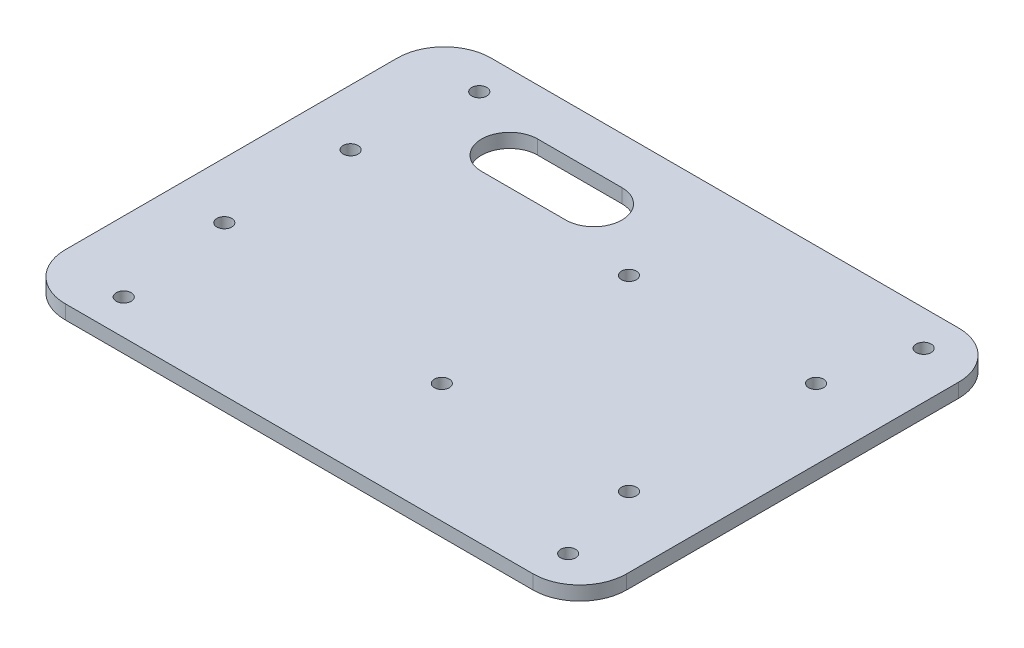
SolidWorks part; units mm, degrees
ref_plane "Front Plane" through (0, 0, 0) normal (0, 0, 1) x (1, 0, 0)
ref_plane "Top Plane" through (0, 0, 0) normal (0, 1, 0) x (1, 0, 0)
ref_plane "Right Plane" through (0, 0, 0) normal (1, 0, 0) x (0, 0, -1)
sketch "Çizim1" plane through (0, 0, 0) normal (0, 1, 0) x (1, 0, 0)
  line L1 (-50, -45.5) -> (50, -45.5)
  line L2 (-60, -35.5) -> (-60, 35.5)
  line L3 (-50, 45.5) -> (50, 45.5)
  line L4 (60, -35.5) -> (60, 35.5)
  line L5 (-60, -45.5) -> (60, 45.5) construction
  line L6 (-60, 45.5) -> (60, -45.5) construction
  arc A0 (50, 45.5) -> (60, 35.5) centre (50, 35.5) cw
  arc A1 (50, -45.5) -> (60, -35.5) centre (50, -35.5) ccw
  arc A2 (-50, -45.5) -> (-60, -35.5) centre (-50, -35.5) cw
  arc A3 (-60, 35.5) -> (-50, 45.5) centre (-50, 35.5) cw
  point P0 (0, 0)
  dimension "D3" = 10
  dimension "D1" = 120
  dimension "D2" = 91
extrude "Yükseklik-Ekstrüzyon1" add sketch "Çizim1" along normal blind 3 contours L2 A3 L3 A0 L4 A1 L1 A2
sketch "Çizim2" plane through (0, 3, 0) normal (0, 1, 0) x (1, 0, 0)
  line L0 (-50, 45.5) -> (50, 45.5) construction
  line L1 (-50, -45.5) -> (50, -45.5) construction
  line L2 (60, -35.5) -> (60, 35.5) construction
  circle A0 centre (50, -38) radius 1.6
  circle A1 centre (50, 38) radius 1.6
  circle A2 centre (-45, 38) radius 1.6
  circle A3 centre (-45, -38) radius 1.6
  dimension "D1" = 3.2
  dimension "D2" = 3.2
  dimension "D3" = 3.2
  dimension "D4" = 3.2
  dimension "D5" = 76
  dimension "D6" = 76
  dimension "D7" = 95
  dimension "D8" = 95
  dimension "D9" = 7.5
  dimension "D10" = 7.5
  dimension "D11" = 7.5
  dimension "D12" = 10
extrude "Kes-Ekstrüzyon1" cut sketch "Çizim2" against normal blind 3
sketch "Çizim3" plane through (0, 3, 0) normal (0, 1, 0) x (1, 0, 0)
  line L0 (60, -35.5) -> (60, 35.5) construction
  line L1 (-50, 45.5) -> (50, 45.5) construction
  circle A0 centre (45, 20) radius 1.6
  circle A1 centre (45, -20) radius 1.6
  circle A2 centre (5, 20) radius 1.6
  circle A3 centre (5, -20) radius 1.6
  dimension "D1" = 3.2
  dimension "D2" = 3.2
  dimension "D3" = 3.2
  dimension "D4" = 3.2
  dimension "D5" = 40
  dimension "D6" = 40
  dimension "D7" = 15
  dimension "D8" = 15
  dimension "D9" = 40
  dimension "D10" = 40
  dimension "D11" = 25.5
  dimension "D12" = 25.5
extrude "Kes-Ekstrüzyon2" cut sketch "Çizim3" against normal blind 3
sketch "Çizim4" plane through (0, 3, 0) normal (0, 1, 0) x (1, 0, 0)
  line L0 (-30, 29.5) -> (-12, 29.5) construction
  line L1 (-30, 35.5) -> (-12, 35.5)
  line L2 (-30, 23.5) -> (-12, 23.5)
  line L3 (-50, 45.5) -> (50, 45.5) construction
  line L4 (-60, -35.5) -> (-60, 35.5) construction
  arc A0 (-30, 35.5) -> (-30, 23.5) centre (-30, 29.5) ccw
  arc A1 (-12, 23.5) -> (-12, 35.5) centre (-12, 29.5) ccw
  point P2 (-21, 29.5)
  dimension "D1" = 6
  dimension "D4" = 30
  dimension "D2" = 18
  dimension "D3" = 10
extrude "Kes-Ekstrüzyon3" cut sketch "Çizim4" against normal blind 3
sketch "Çizim5" plane through (0, 3, 0) normal (0, 1, 0) x (1, 0, 0)
  line L0 (-60, -35.5) -> (-60, 35.5) construction
  line L1 (-50, -45.5) -> (50, -45.5) construction
  line L3 (-50, 45.5) -> (50, 45.5) construction
  circle A0 centre (-48, 13.5) radius 1.6
  circle A1 centre (-48, -13.5) radius 1.6
  dimension "D1" = 3.2
  dimension "D2" = 3.2
  dimension "D3" = 12
  dimension "D4" = 12
  dimension "D5" = 32
  dimension "D6" = 32
extrude "Kes-Ekstrüzyon4" cut sketch "Çizim5" against normal blind 3
